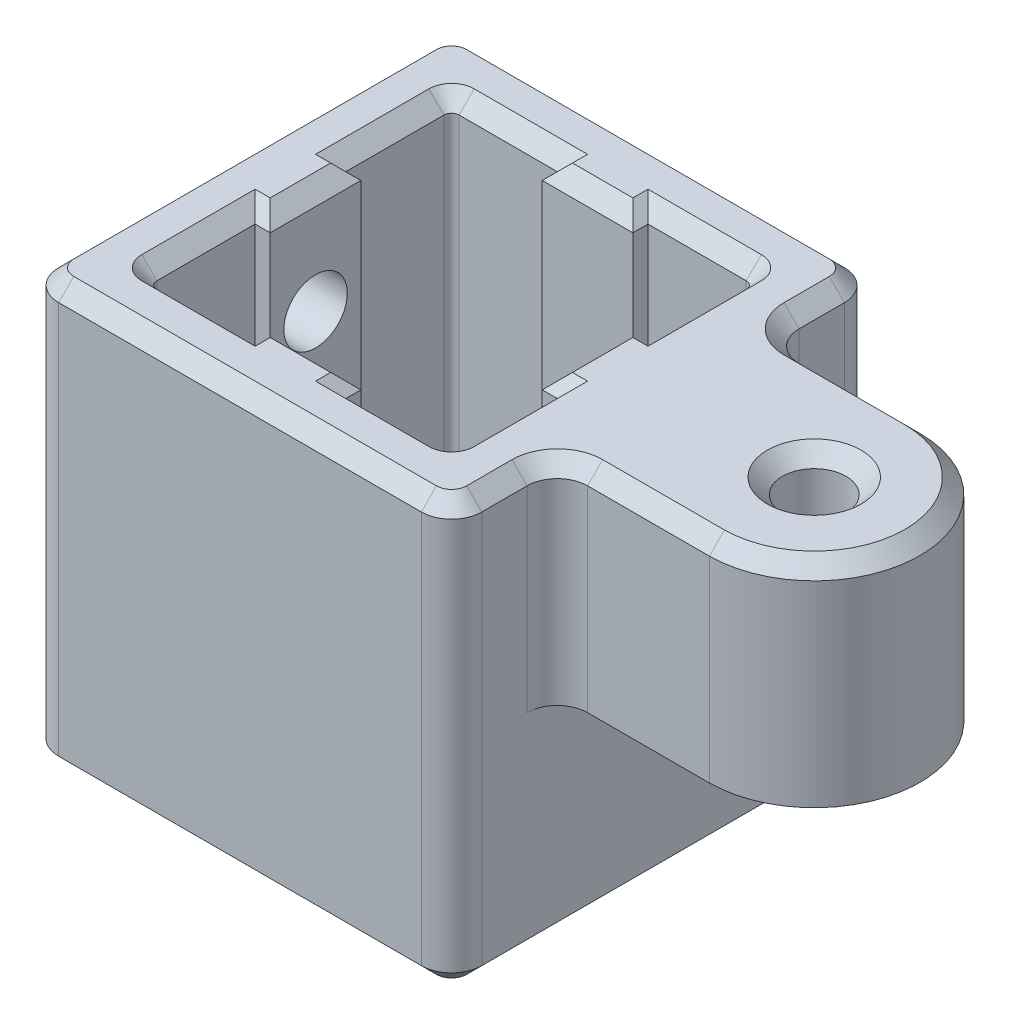
SolidWorks part; units mm, degrees
ref_plane "Alzado" through (0, 0, 0) normal (0, 0, 1) x (1, 0, 0)
ref_plane "Planta" through (0, 0, 0) normal (0, 1, 0) x (1, 0, 0)
ref_plane "Vista lateral" through (0, 0, 0) normal (1, 0, 0) x (0, 0, -1)
sketch "Croquis1" plane through (0, 0, 0) normal (0, 1, 0) x (1, 0, 0)
  line L0 (0, 7) -> (-10, 7)
  line L1 (-10, 7) -> (-10, -6.9997)
  line L2 (-10, -6.9997) -> (0.0625, -6.9997)
  line L3 (0, 0) -> (0, 50000) construction
  line L4 (-10, -17.8118) -> (-10, 49982.1882) construction
  circle A0 centre (0, 0) radius 7 construction
  circle A1 centre (0, 0) radius 2.1
  arc A2 (0, 7) -> (0.0625, -6.9997) centre (0, 0) cw
  point P12 (-10, 7)
  dimension "D1" = 4.2
  dimension "D2" = 14
  dimension "D3" = 10
extrude "Saliente-Extruir1" add sketch "Croquis1" along normal mid plane 14
sketch "Croquis2" plane through (0, 7, 0) normal (0, 1, 0) x (1, 0, 0)
  line L0 (0, 0) -> (-50000, 0) construction
  line L1 (-38, -39.4402) -> (-38, 49960.5598) construction
  line L2 (-10, -200017.8118) -> (-10, 249982.1882) construction
  line L4 (-38, -14) -> (-10, -14)
  line L5 (-38, -14) -> (-38, 14)
  line L6 (-38, 14) -> (-10, 14)
  line L7 (-10, -14) -> (-10, 14)
  line L8 (-38, -14) -> (-10, 14) construction
  line L9 (-38, 14) -> (-10, -14) construction
  line L10 (-34, 10) -> (-14, 10)
  line L11 (-34, 10) -> (-34, -10)
  line L12 (-34, -10) -> (-14, -10)
  line L13 (-14, 10) -> (-14, -10)
  line L14 (-34, 10) -> (-14, -10) construction
  line L15 (-34, -10) -> (-14, 10) construction
  point P7 (-24, 0)
  point P12 (-24, 14)
  point P13 (-24, 0)
  dimension "D1" = 4
  dimension "D2" = 4
  dimension "D3" = 20
extrude "Saliente-Extruir2" add sketch "Croquis2" against normal blind 28
sketch "Croquis3" plane through (0, 7, 0) normal (0, 1, 0) x (1, 0, 0)
  line L0 (-24, 10) -> (-24, -49990) construction
  line L1 (-14, 10) -> (-34, 10) construction
  line L2 (-14, 0) -> (-50014, 0) construction
  line L3 (-14, -10) -> (-14, 10) construction
  line L4 (-27, -10) -> (-21, -9) construction
  line L5 (-27, 9) -> (-21, 9)
  line L6 (-27, 9) -> (-27, 10)
  line L7 (-27, 10) -> (-21, 10)
  line L8 (-21, 9) -> (-21, 10)
  line L9 (-27, 9) -> (-21, 10) construction
  line L10 (-27, 10) -> (-21, 9) construction
  line L11 (-15, -3) -> (-14, -3)
  line L12 (-15, -3) -> (-15, 3)
  line L13 (-15, 3) -> (-14, 3)
  line L14 (-14, -3) -> (-14, 3)
  line L15 (-15, -3) -> (-14, 3) construction
  line L16 (-15, 3) -> (-14, -3) construction
  line L17 (-27, -9) -> (-21, -10) construction
  line L18 (-21, -9) -> (-21, -10)
  line L19 (-27, -10) -> (-21, -10)
  line L20 (-27, -9) -> (-27, -10)
  line L21 (-27, -9) -> (-21, -9)
  line L22 (-33, 3) -> (-34, -3) construction
  line L23 (-33, -3) -> (-34, 3) construction
  line L24 (-34, -3) -> (-34, 3)
  line L25 (-33, 3) -> (-34, 3)
  line L26 (-33, -3) -> (-33, 3)
  line L27 (-33, -3) -> (-34, -3)
  point P4 (-24, 10)
  point P9 (-14, 0)
  point P10 (-24, 9.5)
  point P15 (-14.5, 0)
  point P20 (-24, 9)
  point P21 (-21.4203, 8)
  point P26 (-24, -9.5)
  point P31 (-33.5, 0)
  dimension "D1" = 1
  dimension "D2" = 6
extrude "Saliente-Extruir3" add sketch "Croquis3" against normal through all
fillet "Redondeo1" radius 0.5 4 edges at (-14, -7, 10) (-14, -7, -10) (-34, -7, -10) (-34, -7, 10)
fillet "Redondeo2" radius 2 4 edges at (-38, -7, -14) (-10, -7, -14) (-38, -7, 14) (-10, -7, 14)
fillet "Redondeo3" radius 2 2 edges at (-10, 0, -7) (-10, 0, 6.9997)
chamfer "Chaflán1" distance 1 angle 45 24 edges at (-14.1464, -21, 9.8536) (-14.1464, -21, -9.8536) (-33.8536, -21, -9.8536) (-33.8536, -21, 9.8536) (-24, -21, -14) (-38, -21, 0) (-10, -21, 0) (-24, -21, 14) (-10.5858, -21, 13.4142) (-37.4142, -21, 13.4142) (-10.5858, -21, -13.4142) (-37.4142, -21, -13.4142) (-21, -21, -9.5) (-24, -21, -9) (-27, -21, -9.5) (-14.5, -21, 3) (-15, -21, 0) (-14.5, -21, -3) (-27, -21, 9.5) (-24, -21, 9) (-21, -21, 9.5) (-33, -21, 0) (-33.5, -21, 3) (-33.5, -21, -3)
chamfer "Chaflán3" distance 1 angle 45 39 edges at (-21, 7, -9.5) (-24, 7, -9) (-27, 7, -9.5) (-30.25, 7, -10) (-33.8536, 7, -9.8536) (-34, 7, -6.25) (-33.5, 7, -3) (-33, 7, 0) (-33.5, 7, 3) (-34, 7, 6.25) (-33.8536, 7, 9.8536) (-30.25, 7, 10) (-27, 7, 9.5) (-24, 7, 9) (-21, 7, 9.5) (-17.75, 7, 10) (-14.1464, 7, 9.8536) (-14, 7, 6.25) (-14.5, 7, 3) (-15, 7, 0) (-14.5, 7, -3) (-14, 7, -6.25) (-14.1464, 7, -9.8536) (-17.75, 7, -10) (0, 7, 2.1) (-10.5858, 7, -13.4142) (-10, 7, -10.5) (-9.4142, 7, -7.5858) (-4, 7, -7) (6.9999, 7, -0.0312) (-3.9688, 7, 6.9997) (-9.4142, 7, 7.5855) (-10, 7, 10.4999) (-10.5858, 7, 13.4142) (-24, 7, 14) (-37.4142, 7, 13.4142) (-38, 7, 0) (-37.4142, 7, -13.4142) (-24, 7, -14)
sketch "Croquis4" plane through (-38, 0, 0) normal (-1, 0, 0) x (0, 0, 1)
  line L0 (0, 0) -> (0, -50000) construction
  circle A0 centre (0, 0) radius 2.1
  circle A1 centre (0, -14) radius 2.1
  point P7 (0, 0)
  point P8 (0, 0)
  dimension "D1" = 4.2
  dimension "D2" = 14
extrude "Cortar-Extruir2" cut sketch "Croquis4" against normal up to next
